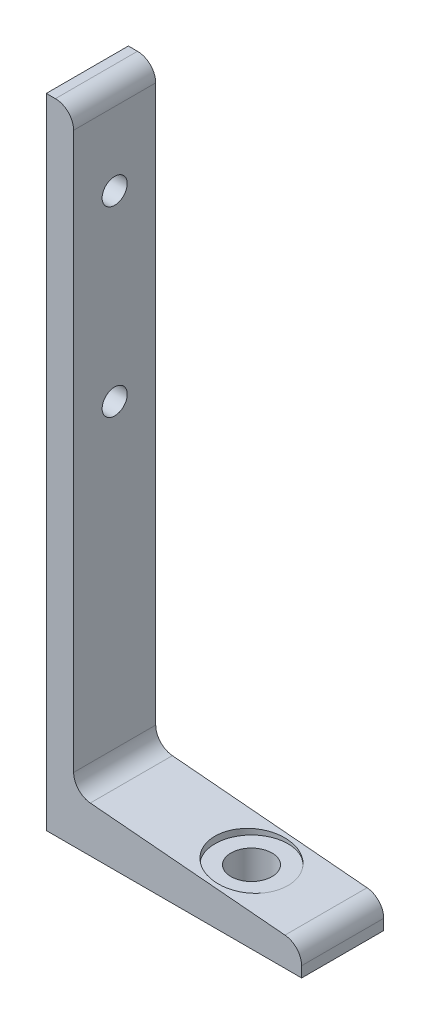
SolidWorks part; units mm, degrees
ref_plane "Front Plane" through (0, 0, 0) normal (0, 0, 1) x (1, 0, 0)
ref_plane "Top Plane" through (0, 0, 0) normal (0, 1, 0) x (1, 0, 0)
ref_plane "Right Plane" through (0, 0, 0) normal (1, 0, 0) x (0, 0, -1)
sketch "Sketch1" plane through (0, 0, 0) normal (0, 0, 1) x (1, 0, 0)
  line L0 (0, 0) -> (0, 140)
  line L1 (6, 140) -> (6, 136) construction
  line L2 (6, 136) -> (6, 14.0398)
  line L3 (9.6514, 10.055) -> (52.3486, 6.3195)
  line L4 (6, 140) -> (0, 140) construction
  line L5 (56, 0) -> (0, 0)
  line L6 (52.3486, 6.3195) -> (56, 6) construction
  line L7 (56, 6) -> (56, 0) construction
  line L8 (0, 140) -> (2, 140)
  line L9 (56, 2.3347) -> (56, 0)
  arc A0 (6, 136) -> (2, 140) centre (2, 136) ccw
  arc A1 (56, 2.3347) -> (52.3486, 6.3195) centre (52, 2.3347) ccw
  arc A2 (6, 14.0398) -> (9.6514, 10.055) centre (10, 14.0398) ccw
  point P2 (6, 138)
  dimension "D1" = 5
  dimension "E" = 6
  dimension "Er" = 4
  dimension "Dr" = 4
  dimension "A" = 140
  dimension "F" = 56
extrude "Boss-Extrude1" add sketch "Sketch1" along normal mid plane 18
sketch "Sketch2" plane through (0, 0, 0) normal (0, 1, 0) x (1, 0, 0)
  line L0 (0, -9) -> (56, -9) construction
  line L2 (36, 0) -> (0, 0) construction
  line L3 (0, -9) -> (0, 9) construction
  line L6 (0, -9) -> (0, 9) construction
  circle A0 centre (36, 0) radius 4.5
  circle A1 centre (36, 0) radius 8 construction
  dimension "L" = 9
  dimension "M" = 16
  dimension "N" = 9
  dimension "G" = 36
extrude "Cut-Extrude1" cut sketch "Sketch2" along normal through all
sketch "Sketch3" plane through (0, 0, 0) normal (0, 1, 0) x (1, 0, 0)
  circle A1 centre (36, 0) radius 8 construction
  circle A2 centre (36, 0) radius 8
extrude "Cut-Extrude2" cut sketch "Sketch3" along normal through all from offset 7
sketch "Sketch4" plane through (0, 0, 0) normal (1, 0, 0) x (0, 0, -1)
  line L0 (0, 0) -> (0, 80) construction
  line L1 (0, 80) -> (0, 120) construction
  circle A0 centre (0, 80) radius 2.75
  circle A1 centre (0, 120) radius 2.75
  dimension "K" = 5.5
  dimension "B" = 80
  dimension "C" = 40
extrude "Cut-Extrude3" cut sketch "Sketch4" along normal through all
